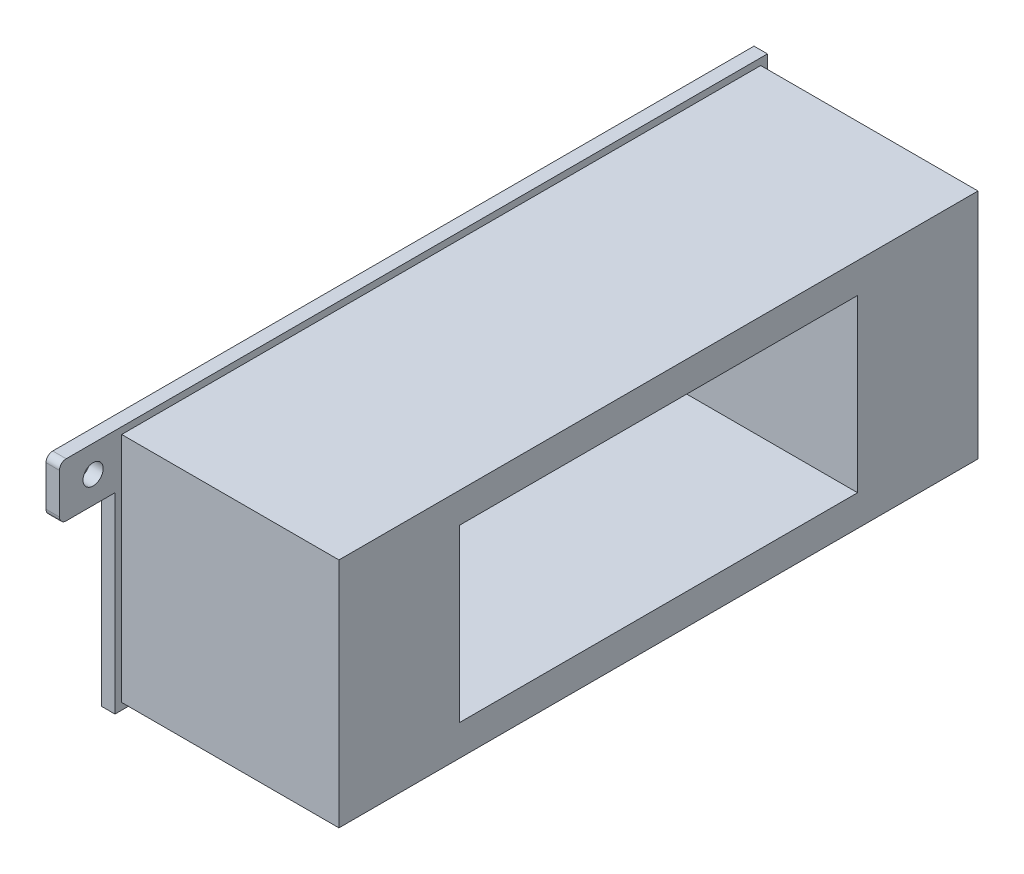
SolidWorks part; units mm, degrees
ref_plane "Front" through (0, 0, 0) normal (0, 0, 1) x (1, 0, 0)
ref_plane "Top" through (0, 0, 0) normal (0, 1, 0) x (1, 0, 0)
ref_plane "Right" through (0, 0, 0) normal (1, 0, 0) x (0, 0, -1)
sketch "Sketch1" plane through (0, 0, 0) normal (0, 0, 1) x (1, 0, 0)
  line L0 (40.8693, 66.8891) -> (40.8693, 30.3891)
  line L5 (40.8693, 30.3891) -> (42.8693, 30.3891)
  line L6 (42.8693, 30.3891) -> (42.8693, 31.3891)
  line L7 (42.8693, 31.3891) -> (75.1693, 31.3891)
  line L8 (75.1693, 31.3891) -> (75.1693, 65.8891)
  line L9 (75.1693, 65.8891) -> (42.8693, 65.8891)
  line L10 (42.8693, 65.8891) -> (42.8693, 66.8891)
  line L11 (42.8693, 66.8891) -> (40.8693, 66.8891)
  dimension "D1" = 2
  dimension "D2" = 2
  dimension "D3" = 1
  dimension "D4" = 1
  dimension "D5" = 36.5
  dimension "D6" = 34.3
extrude "Boss-Extrude1" add sketch "Sketch1" along normal blind 95
sketch "Sketch2" plane through (40.8693, 0, 0) normal (-1, 0, 0) x (0, 0, 1)
  line L0 (-1, 38.3891) -> (-8.25, 38.3891)
  line L9 (0, 30.3891) -> (-8.25, 30.3891)
  line L10 (0, 30.3891) -> (0, 38.3891)
  line L12 (-9.25, 31.3891) -> (-9.25, 37.3891)
  line L13 (95, 66.8891) -> (103.25, 66.8891)
  line L14 (95, 66.8891) -> (95, 58.8891)
  line L16 (104.25, 65.8891) -> (104.25, 59.8891)
  line L18 (0, 38.3891) -> (0, 66.8891)
  line L19 (0, 66.8891) -> (-1, 66.8891)
  line L20 (-1, 38.3891) -> (-1, 66.8891)
  line L22 (95, 58.8891) -> (95, 30.3891)
  line L23 (95, 30.3891) -> (96, 30.3891)
  line L24 (96, 58.8891) -> (96, 30.3891)
  line L25 (96, 58.8891) -> (103.25, 58.8891)
  circle A0 centre (-4.25, 34.3891) radius 1.5
  circle A1 centre (99.25, 62.8891) radius 1.5
  arc A2 (103.25, 58.8891) -> (104.25, 59.8891) centre (103.25, 59.8891) ccw
  arc A3 (104.25, 65.8891) -> (103.25, 66.8891) centre (103.25, 65.8891) ccw
  arc A4 (-8.25, 30.3891) -> (-9.25, 31.3891) centre (-8.25, 31.3891) cw
  arc A5 (-9.25, 37.3891) -> (-8.25, 38.3891) centre (-8.25, 37.3891) cw
  point P22 (104.25, 58.8891)
  point P25 (104.25, 66.8891)
  point P28 (-9.25, 30.3891)
  point P31 (-9.25, 38.3891)
  dimension "D6" = 103.5
  dimension "D7" = 5
  dimension "D8" = 5
  dimension "D11" = 1
  dimension "D1" = 113.5
  dimension "D2" = 9.25
  dimension "D3" = 9.25
  dimension "D4" = 8
  dimension "D5" = 8
  dimension "D9" = 1
  dimension "D10" = 1
extrude "Boss-Extrude2" add sketch "Sketch2" against normal blind 2
sketch "Sketch3" plane through (40.8693, 0, 0) normal (-1, 0, 0) x (0, 0, 1)
  line L0 (-1, 66.8891) -> (-1, 38.3891) construction
  line L5 (17.9, 35.9891) -> (77.08, 35.9891)
  line L6 (17.9, 35.9891) -> (17.9, 61.3891)
  line L7 (17.9, 61.3891) -> (77.08, 61.3891)
  line L8 (77.08, 35.9891) -> (77.08, 61.3891)
  line L9 (96, 30.3891) -> (96, 58.8891) construction
  line L10 (103.25, 66.8891) -> (-1, 66.8891) construction
  line L11 (96, 30.3891) -> (-8.25, 30.3891) construction
  dimension "D1" = 59.18
  dimension "D2" = 25.4
  dimension "D3" = 18.9
  dimension "D4" = 18.92
  dimension "D5" = 5.5
  dimension "D6" = 5.6
extrude "Cut-Extrude1" cut sketch "Sketch3" against normal through all
